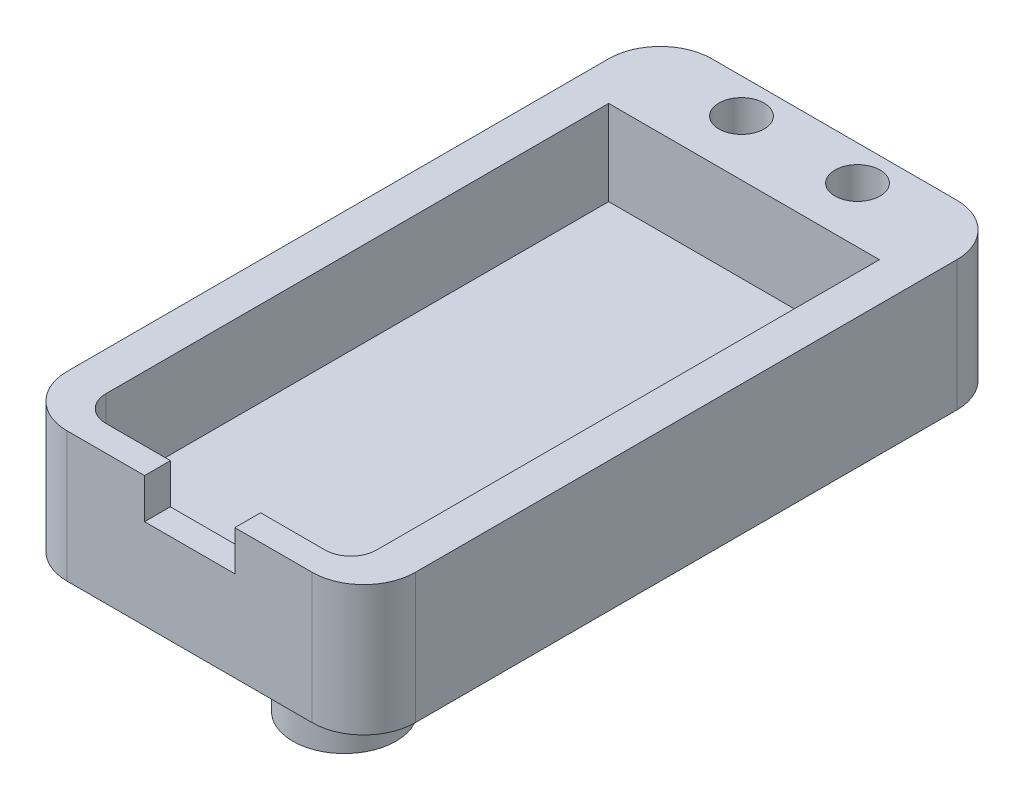
SolidWorks part; units mm, degrees
ref_plane "Front Plane" through (0, 0, 0) normal (0, 0, 1) x (1, 0, 0)
ref_plane "Top Plane" through (0, 0, 0) normal (0, 1, 0) x (1, 0, 0)
ref_plane "Right Plane" through (0, 0, 0) normal (1, 0, 0) x (0, 0, -1)
sketch "Sketch1" plane through (0, 0, 0) normal (0, 1, 0) x (1, 0, 0)
  line L1 (0, 41) -> (27, 41)
  line L2 (0, 41) -> (0, 0)
  line L3 (0, 0) -> (27, 0)
  line L4 (27, 41) -> (27, 0)
  dimension "D1" = 27
  dimension "D2" = 41
extrude "Boss-Extrude1" add sketch "Sketch1" along normal blind 3.5
sketch "Sketch2" plane through (0, 3.5, 0) normal (0, 1, 0) x (1, 0, 0)
  line L0 (27, 41) -> (0, 41) construction
  line L1 (0, 0) -> (3, 0)
  line L2 (0, 0) -> (0, 41)
  line L3 (0, 41) -> (3, 41)
  line L4 (3, 0) -> (3, 41)
  line L5 (0, 0) -> (27, 0) construction
  line L6 (27, 41) -> (24, 41)
  line L7 (27, 41) -> (27, 0)
  line L8 (27, 0) -> (24, 0)
  line L9 (24, 41) -> (24, 0)
  dimension "D2" = 3
extrude "Boss-Extrude2" add sketch "Sketch2" along normal blind 7.5
sketch "Sketch3" plane through (0, 0, 0) normal (0, -1, 0) x (-1, 0, 0)
  line L0 (0, 0) -> (-27, 0) construction
  circle A0 centre (-13.5, 10) radius 4
  point P2 (-13.5, 0)
  dimension "D1" = 8
  dimension "D2" = 10
extrude "Boss-Extrude3" add sketch "Sketch3" along normal blind 10
sketch "Sketch4" plane through (0, 0, -41) normal (0, 0, -1) x (-1, 0, 0)
  line L1 (-27, 11) -> (0, 11)
  line L2 (-27, 11) -> (-27, 0)
  line L3 (-27, 0) -> (0, 0)
  line L4 (0, 11) -> (0, 0)
extrude "Boss-Extrude4" add sketch "Sketch4" along normal blind 2 contours L1 L4 L3 L2
sketch "Sketch5" plane through (0, 0, 0) normal (0, 0, 1) x (1, 0, 0)
  line L1 (0, 11) -> (27, 11)
  line L2 (0, 11) -> (0, 0)
  line L3 (0, 0) -> (27, 0)
  line L4 (27, 11) -> (27, 0)
extrude "Boss-Extrude5" add sketch "Sketch5" along normal blind 2
sketch "Sketch6" plane through (0, 0, 2) normal (0, 0, 1) x (1, 0, 0)
  line L0 (27, 11) -> (0, 11) construction
  line L1 (10, 11) -> (17, 11)
  line L2 (10, 11) -> (10, 7)
  line L3 (10, 7) -> (17, 7)
  line L4 (17, 11) -> (17, 7)
  line L5 (9.5, 0) -> (17.5, 0) construction
  point P6 (13.5, 0)
  point P7 (13.5, 7)
  point P10 (0, 0)
  dimension "D1" = 4
  dimension "D2" = 7
extrude "Cut-Extrude1" cut sketch "Sketch6" against normal up to next
sketch "Sketch7" plane through (0, 0, -43) normal (0, 0, -1) x (-1, 0, 0)
  line L1 (-27, 11) -> (0, 11)
  line L2 (-27, 11) -> (-27, 0)
  line L3 (-27, 0) -> (0, 0)
  line L4 (0, 11) -> (0, 0)
extrude "Boss-Extrude6" add sketch "Sketch7" along normal blind 5
sketch "Sketch8" plane through (0, 11, 0) normal (0, 1, 0) x (1, 0, 0)
  line L0 (0, 48) -> (27, 48) construction
  circle A0 centre (18, 45.3) radius 1.75
  circle A1 centre (9, 45.3) radius 1.75
  point P7 (13.5, 48)
  dimension "D1" = 3.5
  dimension "D2" = 2.7
  dimension "D3" = 9
  dimension "D4" = 4.5
extrude "Cut-Extrude2" cut sketch "Sketch8" against normal through all
sketch "Sketch9" plane through (0, 11, 0) normal (0, 1, 0) x (1, 0, 0)
  line L1 (0, 48) -> (27, 48)
  line L2 (0, 48) -> (0, -2)
  line L3 (0, -2) -> (27, -2)
  line L4 (27, 48) -> (27, -2)
extrude "Cut-Extrude3" cut sketch "Sketch9" against normal blind 0.9
fillet "Fillet1" radius 4 4 edges at (0, 5.05, -48) (27, 5.05, -48) (27, 5.05, 2) (0, 5.05, 2)
fillet "Fillet2" radius 2 2 edges at (24, 6.8, 0) (3, 6.8, 0)
